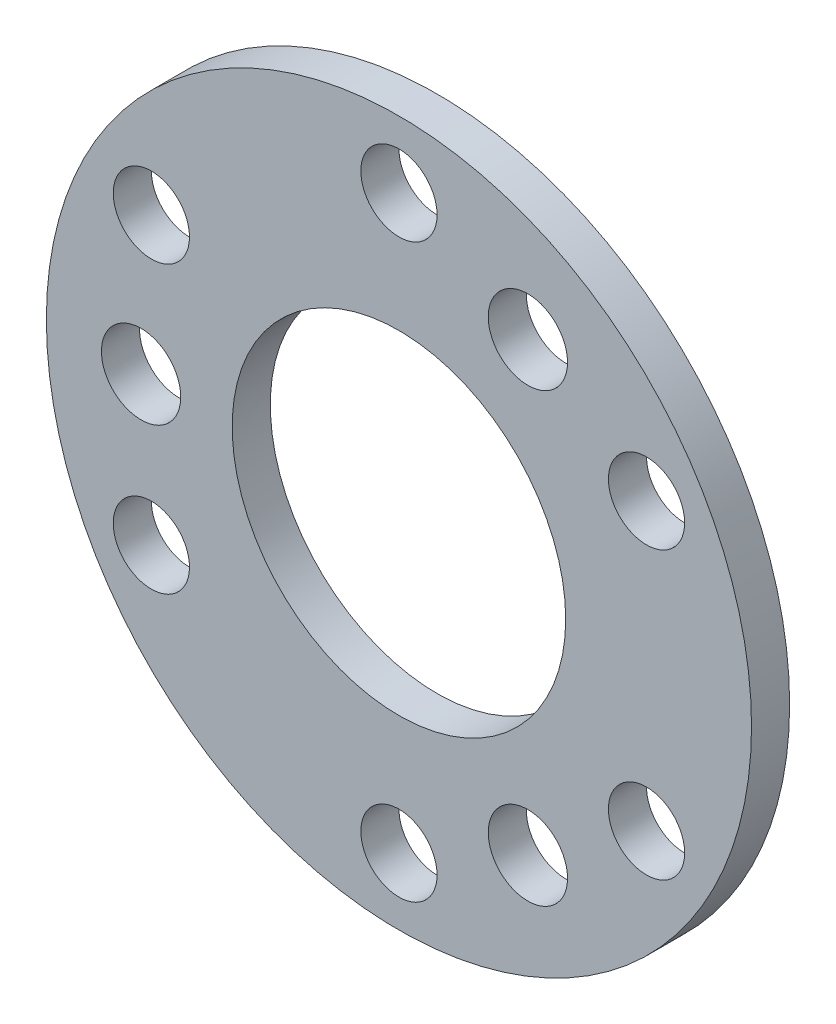
SolidWorks part; units mm, degrees
ref_plane "前视基准面" through (0, 0, 0) normal (0, 0, 1) x (1, 0, 0)
ref_plane "上视基准面" through (0, 0, 0) normal (0, 1, 0) x (1, 0, 0)
ref_plane "右视基准面" through (0, 0, 0) normal (1, 0, 0) x (0, 0, -1)
sketch "草图1" plane through (0, 0, 0) normal (0, 0, 1) x (1, 0, 0)
  line L0 (-0.9852, 0.129) -> (-0.9852, -3.2208) construction
  circle A0 centre (-0.9852, 0.129) radius 15 construction
  circle A1 centre (-0.9852, 0.129) radius 13.53 construction
  circle A2 centre (-0.9852, -14.871) radius 2
  circle A3 centre (-13.9756, -7.371) radius 2
  circle A4 centre (-13.9756, 7.629) radius 2
  circle A5 centre (-0.9852, 15.129) radius 2
  circle A6 centre (12.0052, 7.629) radius 2
  circle A7 centre (12.0052, -7.371) radius 2
  circle A8 centre (-14.5152, 0.129) radius 2.08
  circle A9 centre (5.7798, 11.8463) radius 2.08
  circle A10 centre (5.7798, -11.5883) radius 2.08
  circle A11 centre (-0.9852, 0.129) radius 8.75
  circle A12 centre (-0.9852, 0.129) radius 18.5
extrude "凸台-拉伸1" add sketch "草图1" along normal blind 2 contours A12
sketch "草图2" plane through (0, 0, 0) normal (0, 0, -1) x (-1, 0, 0)
  line L0 (0.9852, 0.129) -> (0.9852, -8.621) construction
  circle A0 centre (0.9852, 0.129) radius 8.75 construction
sketch "草图3" plane through (0, 0, 0) normal (0, 0, -1) x (-1, 0, 0)
  circle A0 centre (0.9852, 0.129) radius 5
sketch "草图4" plane through (0, 0, 2) normal (0, 0, 1) x (1, 0, 0)
  circle A1 centre (-0.9852, 0.129) radius 5
